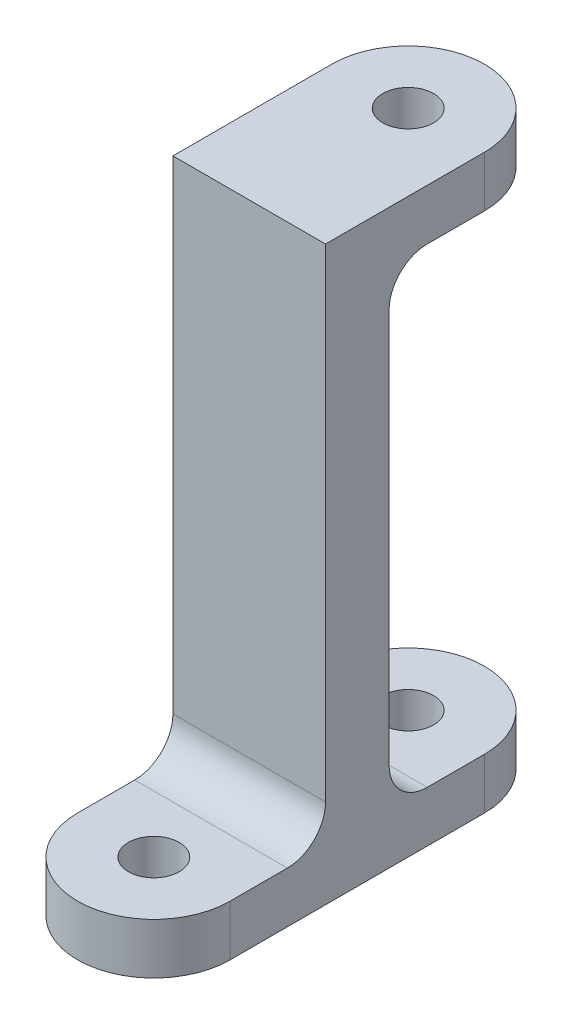
SolidWorks part; units mm, degrees
ref_plane "Front Plane" through (0, 0, 0) normal (0, 0, 1) x (1, 0, 0)
ref_plane "Top Plane" through (0, 0, 0) normal (0, 1, 0) x (1, 0, 0)
ref_plane "Right Plane" through (0, 0, 0) normal (1, 0, 0) x (0, 0, -1)
sketch "Sketch1" plane through (0, 0, 0) normal (0, 1, 0) x (1, 0, 0)
  line L0 (0, 20) -> (0, 0) construction
  line L1 (-6, 20) -> (-6, 0)
  line L2 (6, 20) -> (6, 0)
  circle A0 centre (0, 0) radius 2
  circle A1 centre (0, 20) radius 2
  circle A2 centre (0, 20) radius 6
  circle A3 centre (0, 0) radius 6
  dimension "D1" = 4
  dimension "D2" = 4
  dimension "D3" = 4
  dimension "D4" = 4
  dimension "D5" = 20
extrude "Boss-Extrude1" add sketch "Sketch1" along normal blind 4
sketch "Sketch2" plane through (0, 4, 0) normal (0, 1, 0) x (1, 0, 0)
  line L0 (-6, 20) -> (6, 0) construction
  line L1 (-6, 20) -> (-6, 0) construction
  line L2 (6, 12.5) -> (-6, 12.5)
  line L3 (6, 12.5) -> (6, 7.5)
  line L4 (6, 7.5) -> (-6, 7.5)
  line L5 (-6, 12.5) -> (-6, 7.5)
  line L6 (6, 12.5) -> (-6, 7.5) construction
  line L7 (6, 7.5) -> (-6, 12.5) construction
  point P4 (0, 10)
  dimension "D1" = 5
extrude "Boss-Extrude2" add sketch "Sketch2" along normal blind 37 contours L3 L2 L5 L4
sketch "Sketch3" plane through (0, 41, 0) normal (0, 1, 0) x (1, 0, 0)
  line L3 (-6, 12.5) -> (6, 12.5)
  line L4 (-6, 7.5) -> (6, 7.5)
  line L5 (6, 7.5) -> (6, 12.5)
  line L6 (6, 12.5) -> (-6, 12.5)
  line L7 (-6, 12.5) -> (-6, 7.5)
  line L8 (-6, 7.5) -> (6, 7.5)
  line L9 (6, 7.5) -> (6, 12.5)
  line L10 (6, 12.5) -> (-6, 12.5)
  line L11 (-6, 12.5) -> (-6, 7.5)
  line L12 (6, 12.5) -> (6, 20)
  line L13 (-6, 20) -> (-6, 12.5)
  line L14 (-6, 12.5) -> (6, 12.5)
  line L15 (6, 12.5) -> (6, 20)
  line L16 (-6, 20) -> (-6, 12.5)
  circle A0 centre (0, 20) radius 2
  arc A1 (6, 20) -> (-6, 20) centre (0, 20) ccw
  arc A2 (6, 20) -> (-6, 20) centre (0, 20) ccw
  line M9 (-6, 7.5) -> (6, 7.5)
  line M10 (6, 7.5) -> (6, 12.5)
  line M11 (6, 12.5) -> (-6, 12.5)
  line M12 (-6, 12.5) -> (-6, 7.5)
  dimension "D1" = 0
  dimension "D2" = 0
extrude "Boss-Extrude3" add sketch "Sketch3" along normal blind 4 contours L15 A2 L16 A0 M11 | M12 M9 M10 M11
fillet "Fillet1" radius 3 3 edges at (0, 41, -12.5) (0, 4, -7.5) (0, 4, -12.5)
